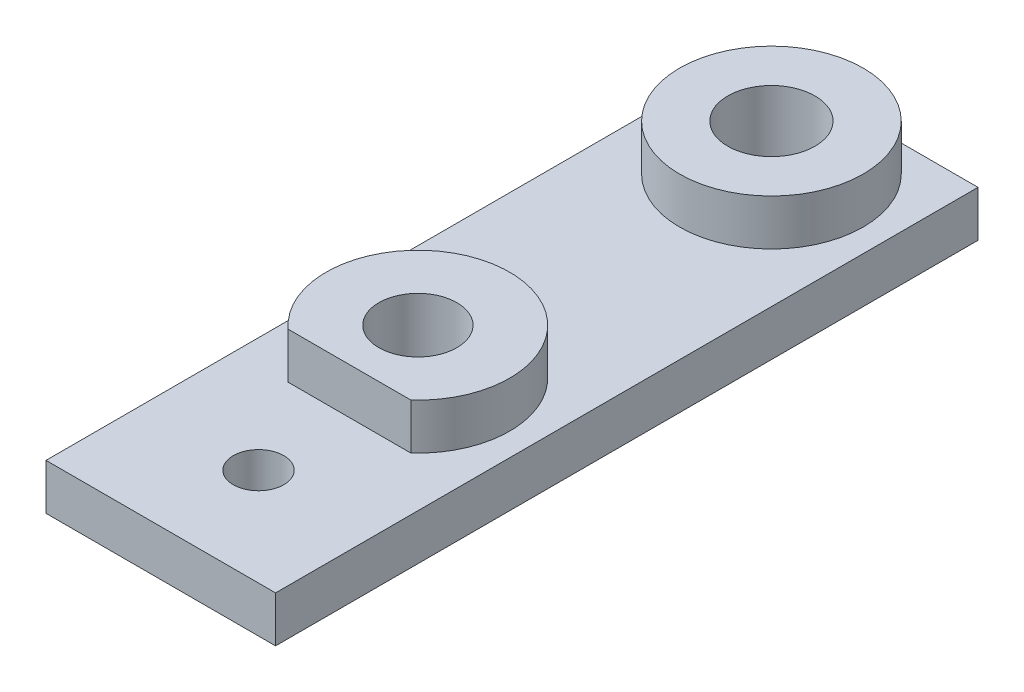
SolidWorks part; units mm, degrees
ref_plane "前视基准面" through (0, 0, 0) normal (0, 0, 1) x (1, 0, 0)
ref_plane "上视基准面" through (0, 0, 0) normal (0, 1, 0) x (1, 0, 0)
ref_plane "右视基准面" through (0, 0, 0) normal (1, 0, 0) x (0, 0, -1)
sketch "草图1" plane through (0, 0, 0) normal (0, 1, 0) x (1, 0, 0)
  line L1 (-39.4811, 27.2736) -> (-14.4811, 27.2736)
  line L2 (-39.4811, 27.2736) -> (-39.4811, -49.2264)
  line L3 (-39.4811, -49.2264) -> (-14.4811, -49.2264)
  line L4 (-14.4811, 27.2736) -> (-14.4811, -49.2264)
  line L5 (-26.9811, -49.2264) -> (-26.9811, 27.2736) construction
  line L6 (-39.4811, -10.9764) -> (-14.4811, -10.9764) construction
  circle A0 centre (-26.9811, 17.2736) radius 4.75
  circle A1 centre (-26.9811, -21.2264) radius 4.25
  point P0 (-26.9811, -10.9764)
  point P8 (0, 0)
  point P9 (0, 0)
  point P10 (0, 0)
  point P13 (-6.6792, -6.7798)
  dimension "D6" = 9.5
  dimension "D7" = 8.5
  dimension "D1" = 10
  dimension "D2" = 38.5
  dimension "D3" = 25
  dimension "D5" = 76.5
extrude "凸台-拉伸1" add sketch "草图1" along normal blind 5
sketch "草图2" plane through (0, 0, 0) normal (0, -1, 0) x (-1, 0, 0)
  line L0 (26.9811, -21.2264) -> (26.9811, -49.2264) construction
  line L1 (39.4811, -49.2264) -> (14.4811, -49.2264) construction
  circle A0 centre (26.9811, -38.58) radius 2.75
  point P7 (26.9811, -38.58)
  dimension "D1" = 5.5
extrude "切除-拉伸1" cut sketch "草图2" against normal through all
sketch "草图3" plane through (0, 5, 0) normal (0, 1, 0) x (1, 0, 0)
  line L0 (-33.6585, -28.6704) -> (-20.3038, -28.6704)
  circle A0 centre (-26.9811, 17.2736) radius 4.75 construction
  circle A1 centre (-26.9811, 17.2736) radius 4.75
  circle A2 centre (-26.9811, 17.2736) radius 10
  arc A3 (-20.3038, -28.6704) -> (-33.6585, -28.6704) centre (-26.9811, -21.2264) ccw
  circle A4 centre (-26.9811, -21.2264) radius 4.25 construction
  circle A5 centre (-26.9811, -21.2264) radius 4.25
  dimension "D1" = 20
  dimension "D2" = 20
extrude "凸台-拉伸2" add sketch "草图3" along normal blind 5
